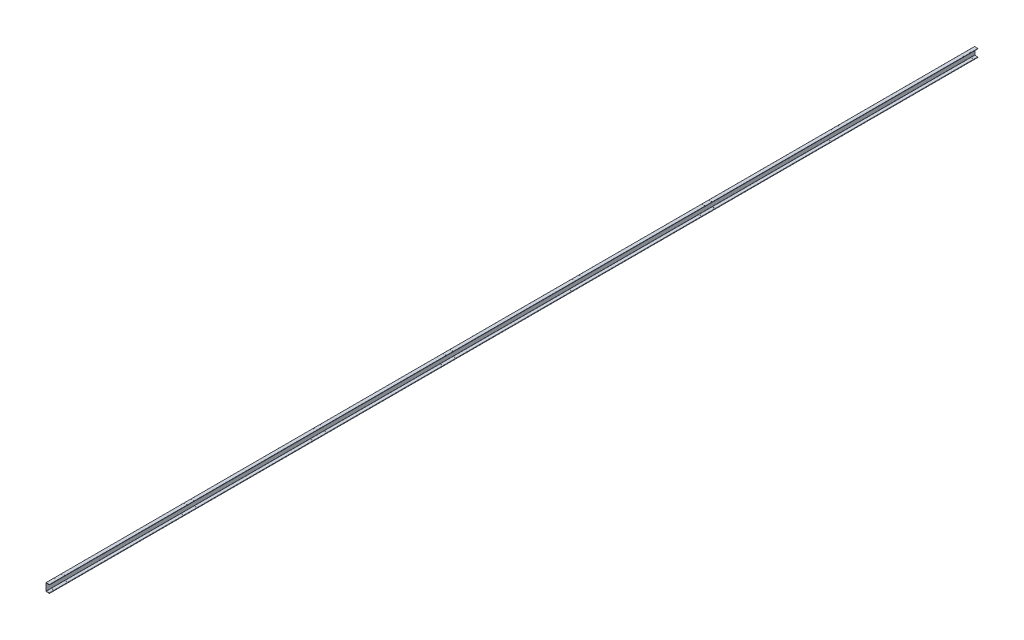
SolidWorks part; units mm, degrees
material "Gray Cast Iron"
ref_plane "Front Plane" through (0, 0, 0) normal (0, 0, 1) x (1, 0, 0)
ref_plane "Top Plane" through (0, 0, 0) normal (0, 1, 0) x (1, 0, 0)
ref_plane "Right Plane" through (0, 0, 0) normal (1, 0, 0) x (0, 0, -1)
sketch "Sketch1" plane through (0, 0, 0) normal (0, 0, 1) x (1, 0, 0)
  line L0 (0, 50) -> (0, -50)
  line L1 (0, -50) -> (45, -50)
  line L2 (0, 50) -> (45, 50)
  line L3 (45, 50) -> (45, 44.9)
  line L4 (45, 44.9) -> (3, 44.9)
  line L5 (45, -50) -> (45, -44.9)
  line L6 (45, -44.9) -> (3, -44.9)
  line L7 (3, -44.9) -> (3, 44.9)
  point P4 (0, 0)
  dimension "D1" = 100
  dimension "D2" = 45
  dimension "D3" = 45
  dimension "D4" = 5.1
  dimension "D5" = 42
  dimension "D6" = 89.8
extrude "Boss-Extrude1" add sketch "Sketch1" along normal blind 12000
fillet "Fillet1" radius 3 2 edges at (45, -44.9, 6000) (45, 44.9, 6000)
fillet "Fillet2" radius 1 4 edges at (0, 50, 6000) (0, -50, 6000) (45, -50, 6000) (45, 50, 6000)
fillet "Fillet3" radius 1 2 edges at (3, -44.9, 6000) (3, 44.9, 6000)
sketch "Sketch4" plane through (0, -50, 0) normal (0, -1, 0) x (1, 0, 0)
  line L0 (22.5, 12000) -> (22.5, 0) construction
  line L1 (1, 12000) -> (44, 12000) construction
  line L2 (1, 0) -> (44, 0) construction
  circle A2 centre (22.5, 50) radius 3
  circle A3 centre (22.5, 223) radius 3
  circle A4 centre (22.5, 1723) radius 3
  circle A5 centre (22.5, 1896) radius 3
  circle A6 centre (22.5, 3396) radius 3
  circle A7 centre (22.5, 3569) radius 3
  circle A8 centre (22.5, 5069) radius 3
  circle A9 centre (22.5, 5242) radius 3
  circle A10 centre (22.5, 6742) radius 3
  circle A11 centre (22.5, 6915) radius 3
  circle A12 centre (22.5, 8415) radius 3
  circle A13 centre (22.5, 8588) radius 3
  circle A14 centre (22.5, 10088) radius 3
  circle A15 centre (22.5, 10261) radius 3
  circle A16 centre (22.5, 11761) radius 3
  circle A17 centre (22.5, 11934) radius 3
  dimension "D1" = 173
  dimension "D2" = 1500
  dimension "D3" = 6
  dimension "D4" = 50
  dimension "D5" = 173
  dimension "D6" = 6
  dimension "D7" = 173
  dimension "D8" = 1500
  dimension "D9" = 6
  dimension "D10" = 173
  dimension "D11" = 1500
  dimension "D12" = 6
  dimension "D13" = 173
  dimension "D14" = 1500
  dimension "D15" = 6
  dimension "D16" = 173
  dimension "D17" = 1500
  dimension "D18" = 6
  dimension "D19" = 173
  dimension "D20" = 1500
  dimension "D21" = 6
  dimension "D22" = 173
  dimension "D23" = 1500
  dimension "D24" = 6
extrude "Cut-Extrude4" cut sketch "Sketch4" against normal up to next
sketch "Sketch5" plane through (0, 50, 0) normal (0, 1, 0) x (1, 0, 0)
  line L0 (44, -136.5012) -> (1, -136.5012) construction
  line L1 (957.5, -136.5012) -> (12.5, -136.5012) construction
  line L2 (44, -12000) -> (44, 0) construction
  line L3 (1, 0) -> (1, -12000) construction
  line L4 (22.5, 0) -> (22.5, -12000) construction
  line L5 (44, 0) -> (1, 0) construction
  line L6 (44, -12000) -> (1, -12000) construction
  line L7 (44, -1809.5012) -> (1, -1809.5012) construction
  line L8 (44, -3482.5012) -> (1, -3482.5012) construction
  line L9 (44, -5155.5012) -> (1, -5155.5012) construction
  line L10 (44, -6828.5012) -> (1, -6828.5012) construction
  line L11 (44, -8501.5012) -> (1, -8501.5012) construction
  line L12 (44, -10174.5012) -> (1, -10174.5012) construction
  line L13 (1, -11847.5012) -> (44, -11847.5012) construction
  circle A0 centre (37.5, -181.5012) radius 3
  circle A1 centre (7.5, -181.5012) radius 3
  circle A2 centre (7.5, -91.5012) radius 3
  circle A3 centre (37.5, -91.5012) radius 3
  circle A4 centre (37.5, -1854.5012) radius 3
  circle A5 centre (7.5, -1854.5012) radius 3
  circle A6 centre (7.5, -1764.5012) radius 3
  circle A7 centre (37.5, -1764.5012) radius 3
  circle A8 centre (37.5, -3527.5012) radius 3
  circle A9 centre (7.5, -3527.5012) radius 3
  circle A10 centre (7.5, -3437.5012) radius 3
  circle A11 centre (37.5, -3437.5012) radius 3
  circle A12 centre (37.5, -5200.5012) radius 3
  circle A13 centre (7.5, -5200.5012) radius 3
  circle A14 centre (7.5, -5110.5012) radius 3
  circle A15 centre (37.5, -5110.5012) radius 3
  circle A16 centre (37.5, -6873.5012) radius 3
  circle A17 centre (7.5, -6873.5012) radius 3
  circle A18 centre (7.5, -6783.5012) radius 3
  circle A19 centre (37.5, -6783.5012) radius 3
  circle A20 centre (37.5, -8546.5012) radius 3
  circle A21 centre (7.5, -8546.5012) radius 3
  circle A22 centre (7.5, -8456.5012) radius 3
  circle A23 centre (37.5, -8456.5012) radius 3
  circle A24 centre (37.5, -10219.5012) radius 3
  circle A25 centre (7.5, -10219.5012) radius 3
  circle A26 centre (7.5, -10129.5012) radius 3
  circle A27 centre (37.5, -10129.5012) radius 3
  circle A28 centre (7.5, -11802.5012) radius 3
  circle A29 centre (37.5, -11802.5012) radius 3
  circle A30 centre (37.5, -11892.5012) radius 3
  circle A31 centre (7.5, -11892.5012) radius 3
  dimension "D1" = 45
  dimension "D2" = 45
  dimension "D3" = 15
  dimension "D4" = 15
  dimension "D5" = 6
  dimension "D6" = 1673
  dimension "D7" = 45
  dimension "D8" = 45
  dimension "D9" = 15
  dimension "D10" = 30
  dimension "D11" = 6
  dimension "D13" = 45
  dimension "D14" = 6
  dimension "D15" = 45
  dimension "D16" = 15
  dimension "D17" = 30
  dimension "D19" = 45
  dimension "D20" = 45
  dimension "D21" = 15
  dimension "D22" = 6
  dimension "D23" = 30
  dimension "D25" = 45
  dimension "D26" = 45
  dimension "D27" = 6
  dimension "D28" = 15
  dimension "D29" = 30
  dimension "D31" = 45
  dimension "D32" = 45
  dimension "D33" = 15
  dimension "D34" = 30
  dimension "D35" = 6
  dimension "D37" = 45
  dimension "D38" = 45
  dimension "D39" = 15
  dimension "D40" = 6
  dimension "D41" = 30
  dimension "D43" = 45
  dimension "D45" = 15
  dimension "D46" = 30
  dimension "D47" = 6
  dimension "D12" = 1673
  dimension "D18" = 1673
  dimension "D24" = 1673
  dimension "D30" = 1673
  dimension "D36" = 1673
  dimension "D42" = 1673
  dimension "D44" = 45
extrude "Cut-Extrude5" cut sketch "Sketch5" against normal blind 10
